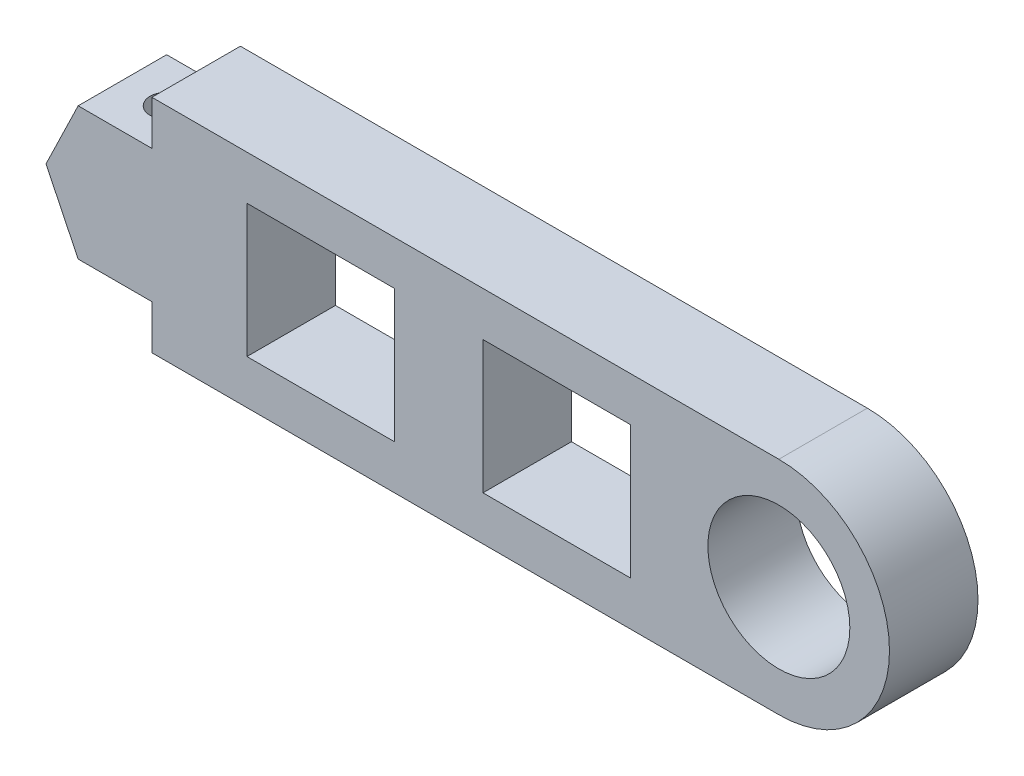
SolidWorks part; units mm, degrees
ref_plane "Front Plane" through (0, 0, 0) normal (0, 0, 1) x (1, 0, 0)
ref_plane "Top Plane" through (0, 0, 0) normal (0, 1, 0) x (1, 0, 0)
ref_plane "Right Plane" through (0, 0, 0) normal (1, 0, 0) x (0, 0, -1)
sketch "Sketch1" plane through (0, 0, 0) normal (0, 0, 1) x (1, 0, 0)
  line L0 (-44.3046, 0) -> (-14.3589, 0) construction
  line L1 (55, 0) -> (-55, 0) construction
  line L2 (0, 15) -> (85, 15)
  line L3 (0, -15) -> (85, -15)
  line L4 (0, 15) -> (0, 9)
  line L5 (0, -55) -> (0, 55) construction
  line L6 (0, 9) -> (-10, 9)
  line L7 (-10, 9) -> (-14.3589, 0)
  line L8 (-14.3589, 0) -> (-10, -9)
  line L9 (-10, -9) -> (0, -9)
  line L10 (0, -9) -> (0, -15)
  line L11 (75.375, 0) -> (85, 0) construction
  line L13 (12.8844, 9) -> (32.8844, 9)
  line L14 (12.8844, 9) -> (12.8844, -9)
  line L15 (12.8844, -9) -> (32.8844, -9)
  line L16 (32.8844, 9) -> (32.8844, -9)
  line L17 (44.8844, 9) -> (64.8844, 9)
  line L18 (44.8844, 9) -> (44.8844, -9)
  line L19 (44.8844, -9) -> (64.8844, -9)
  line L20 (64.8844, 9) -> (64.8844, -9)
  arc A1 (85, -15) -> (85, 15) centre (85, 0) ccw
  circle A2 centre (85, 0) radius 9.625
  point P5 (0.4795, 0)
  dimension "D1" = 15
  dimension "D2" = 85
  dimension "D3" = 10
  dimension "D4" = 6
  dimension "D5" = 10
  dimension "D6" = 6
  dimension "D7" = 10
  dimension "D8" = 18
  dimension "D9" = 20
  dimension "D10" = 20
  dimension "D11" = 18
  dimension "D12" = 12
extrude "Boss-Extrude1" add sketch "Sketch1" along normal blind 12
sketch "Sketch2" plane through (0, -9, 0) normal (0, -1, 0) x (1, 0, 0)
  line L0 (-10, 12) -> (0, 12) construction
  line L1 (0, -55) -> (0, 55) construction
  circle A0 centre (-4, 6) radius 2.25
  point P4 (0, 0)
  point P6 (-1.0971, 4.1296)
  dimension "D1" = 4.5
  dimension "D2" = 6
  dimension "D3" = 4
extrude "Cut-Extrude1" cut sketch "Sketch2" against normal through all
